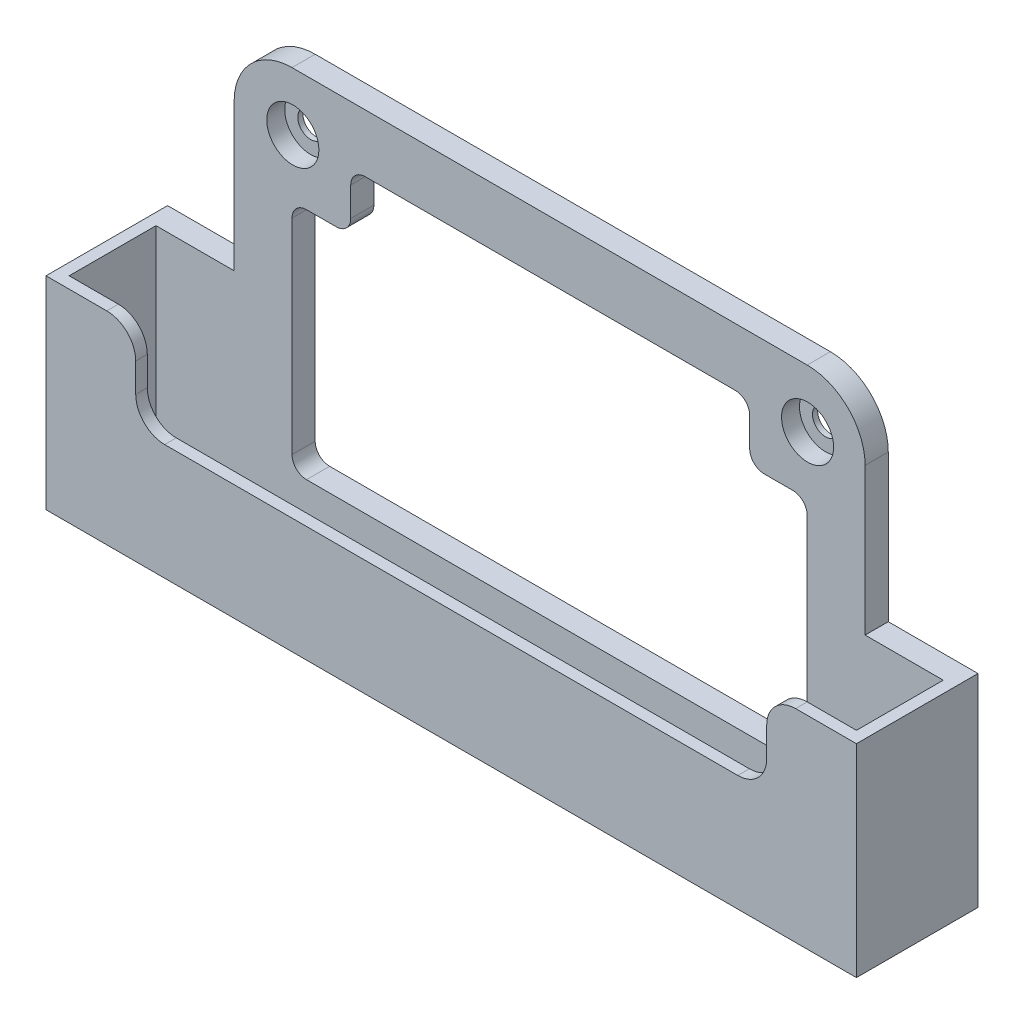
SolidWorks part; units mm, degrees
ref_plane "Front Plane" through (0, 0, 0) normal (0, 0, 1) x (1, 0, 0)
ref_plane "Top Plane" through (0, 0, 0) normal (0, 1, 0) x (1, 0, 0)
ref_plane "Right Plane" through (0, 0, 0) normal (1, 0, 0) x (0, 0, -1)
sketch "Sketch1" plane through (0, 0, 0) normal (0, 0, 1) x (1, 0, 0)
  line L1 (54.5, -70) -> (-54.5, -70)
  line L2 (54.5, -70) -> (54.5, 70)
  line L3 (54.5, 70) -> (-54.5, 70)
  line L4 (-54.5, -70) -> (-54.5, 70)
  line L5 (54.5, -70) -> (-54.5, 70) construction
  line L6 (54.5, 70) -> (-54.5, -70) construction
  point P0 (0, 0)
  point P6 (-44.5, -9.7579)
  point P7 (44.5, -9.7579)
  point P8 (19.5, 58.6849)
  point P9 (-19.5, 58.6849)
  dimension "D1" = 140
  dimension "D2" = 109
  dimension "D3" = 10
  dimension "D4" = 10
  dimension "D5" = 89
  dimension "D6" = 25
  dimension "D7" = 25
extrude "Boss-Extrude1" add sketch "Sketch1" along normal blind 4
hole_wizard "CBORE for M4 Pan Head Machine Screw1" positions "Sketch4" profile "Sketch2" counterbore size "M4" standard "ANSI Metric" end condition through all
sketch "Sketch4" plane through (0, 0, 4) normal (0, 0, 1) x (1, 0, 0)
  point P0 (-19.4083, 58.522)
  point P2 (19.4083, 58.522)
  point P4 (-44.3618, -9.6051)
  point P6 (44.5599, -9.6051)
sketch "Sketch2" plane through (-19.4083, 58.522, 4) normal (1, 0, 0) x (0, -1, 0)
  line L0 (0, 0) -> (0, 4)
  line L1 (0, 4) -> (2.25, 4)
  line L3 (2.25, 4) -> (2.25, 3.1)
  line L4 (2.25, 3.1) -> (4.5, 3.1)
  line L5 (4.5, 3.1) -> (4.5, 0)
  line L7 (4.5, 0) -> (0, 0)
  line L11 (0, -6.35) -> (0, 107.95) construction
  dimension "Thru Hole Dia." = 4.5
  dimension "Thru Hole Depth" = 4
  dimension "C'Bore Dia." = 9
  dimension "C'Bore Depth" = 3.1
sketch "Sketch6" plane through (0, 0, 4) normal (0, 0, 1) x (1, 0, 0)
  line L0 (-29.4083, 70) -> (-29.4083, 0.3949)
  line L1 (54.5, 70) -> (-54.5, 70) construction
  line L2 (-29.4083, 0.3949) -> (-54.5, 0.3949)
  line L3 (-54.5, 70) -> (-54.5, -70) construction
  line L4 (-54.5, 0.3949) -> (-54.5, 70)
  line L5 (-54.5, 70) -> (-29.4083, 70)
  line L6 (29.4083, 70) -> (29.4083, 0.3949)
  line L7 (29.4083, 0.3949) -> (54.5, 0.3949)
  line L8 (54.5, -70) -> (54.5, 70) construction
  line L9 (54.5, 0.3949) -> (54.5, 70)
  line L10 (54.5, 70) -> (29.4083, 70)
  circle A0 centre (-19.4083, 58.522) radius 2.25 construction
  circle A1 centre (19.4083, 58.522) radius 2.25 construction
  circle A2 centre (-44.3618, -9.6051) radius 2.25 construction
  circle A3 centre (44.5599, -9.6051) radius 2.25 construction
  dimension "D1" = 10
  dimension "D2" = 10
  dimension "D3" = 10
  dimension "D4" = 10
extrude "Cut-Extrude1" cut sketch "Sketch6" against normal through all
sketch "Sketch7" plane through (0, 0, 4) normal (0, 0, 1) x (1, 0, 0)
  line L0 (-70, -70) -> (70, -70)
  line L1 (70, -70) -> (70, -35)
  line L2 (70, -35) -> (-70, -35)
  line L3 (-70, -35) -> (-70, -70)
  point P3 (0, -70)
  dimension "D1" = 140
  dimension "D2" = 35
extrude "Boss-Extrude2" add sketch "Sketch7" against normal through all
fillet "Fillet1" radius 10 4 edges at (-54.5, 0.3949, 2) (54.5, 0.3949, 2) (29.4083, 70, 2) (-29.4083, 70, 2)
sketch "Sketch8" plane through (0, 0, 4) normal (0, 0, 1) x (1, 0, 0)
  line L0 (-70, -35) -> (-70, -70)
  line L1 (-70, -70) -> (70, -70)
  line L2 (70, -70) -> (70, -35)
  line L3 (70, -35) -> (68, -35)
  line L4 (70, -35) -> (54.5, -35) construction
  line L5 (68, -35) -> (68, -68)
  line L6 (68, -68) -> (-68, -68)
  line L7 (-68, -68) -> (-68, -35)
  line L8 (-54.5, -35) -> (-70, -35) construction
  line L9 (-68, -35) -> (-70, -35)
  dimension "D1" = 2
  dimension "D2" = 2
  dimension "D3" = 2
extrude "Boss-Extrude3" add sketch "Sketch8" along normal blind 15
sketch "Sketch9" plane through (-70, 0, 0) normal (-1, 0, 0) x (0, 0, 1)
  line L0 (19, -35) -> (19, -70)
  line L1 (19, -70) -> (21, -70)
  line L2 (21, -70) -> (21, -35)
  line L3 (21, -35) -> (19, -35)
  dimension "D1" = 2
extrude "Boss-Extrude4" add sketch "Sketch9" against normal through all
sketch "Sketch10" plane through (0, 0, 4) normal (0, 0, 1) x (1, 0, 0)
  line L0 (-19.4083, 48.522) -> (-9.4083, 48.522)
  line L1 (19.4083, 48.522) -> (19.4083, -9.6051)
  line L2 (19.4083, -9.6051) -> (34.5599, -9.6051)
  line L3 (34.5599, -9.6051) -> (34.5599, -19.6051)
  line L4 (34.5599, -19.6051) -> (44.5, -19.6051)
  line L5 (44.5, -19.6051) -> (44.5, -60)
  line L6 (44.5, -60) -> (-44.5, -60)
  line L7 (-44.5, -60) -> (-44.5, -19.6051)
  line L8 (-44.5, -19.6051) -> (-34.3618, -19.6051)
  line L9 (-34.3618, -19.6051) -> (-34.3618, -9.6051)
  line L10 (-34.3618, -9.6051) -> (-19.4083, -9.6051)
  line L11 (-19.4083, -9.6051) -> (-19.4083, 48.522)
  line L12 (-29.4083, 0.3949) -> (-29.4083, 60) construction
  line L13 (29.4083, 60) -> (29.4083, 0.3949) construction
  line L14 (29.4083, 0.3949) -> (44.5, 0.3949) construction
  line L15 (-44.5, 0.3949) -> (-29.4083, 0.3949) construction
  line L16 (54.5, -35) -> (54.5, -9.6051) construction
  line L17 (-54.5, -9.6051) -> (-54.5, -35) construction
  line L18 (-54.5, -9.6051) -> (-54.5, -35) construction
  line L19 (70, -70) -> (-70, -70) construction
  line L20 (-9.4083, 48.522) -> (-9.4083, 60)
  line L21 (-9.4083, 60) -> (9.4083, 60)
  line L22 (9.4083, 60) -> (9.4083, 48.522)
  line L23 (9.4083, 48.522) -> (19.4083, 48.522)
  line L24 (19.4083, 70) -> (-19.4083, 70) construction
  circle A0 centre (-19.4083, 58.522) radius 4.5 construction
  circle A1 centre (44.5599, -9.6051) radius 2.25 construction
  circle A2 centre (-44.3618, -9.6051) radius 2.25 construction
  circle A3 centre (-19.4083, 58.522) radius 2.25 construction
  circle A4 centre (19.4083, 58.522) radius 2.25 construction
  dimension "D1" = 10
  dimension "D2" = 10
  dimension "D3" = 10
  dimension "D4" = 10
  dimension "D5" = 10
  dimension "D6" = 10
  dimension "D7" = 10
  dimension "D8" = 10
  dimension "D9" = 10
  dimension "D10" = 10
  dimension "D11" = 10
  dimension "D12" = 10
  dimension "D13" = 10
  dimension "D14" = 10
  dimension "D15" = 10
extrude "Cut-Extrude3" cut sketch "Sketch10" against normal through all
sketch "Sketch11" plane through (0, 0, 21) normal (0, 0, 1) x (1, 0, 0)
  line L0 (-54.5, -35) -> (-54.5, -50)
  line L1 (70, -35) -> (-70, -35) construction
  line L2 (-54.5, -50) -> (54.5, -50)
  line L3 (54.5, -50) -> (54.5, -35)
  line L4 (54.5, -35) -> (-54.5, -35)
  line L7 (-54.5, -9.6051) -> (-54.5, -35) construction
  line L8 (54.5, -35) -> (54.5, -9.6051) construction
  line L9 (70, -70) -> (-70, -70) construction
  dimension "D1" = 0
  dimension "D2" = 0
  dimension "D3" = 20
extrude "Cut-Extrude4" cut sketch "Sketch11" against normal up to surface (2 mm away) up to face at (17, -51.5, 19)
fillet "Fillet6" radius 5 5 edges at (-54.5, -50, 20) (54.5, -50, 20) (54.5, -35, 20) (-54.5, -35, 20)
sketch "Sketch13" plane through (0, 0, 0) normal (1, 0, 0) x (0, 0, -1)
  line L0 (0, 0.3949) -> (-4, 0.3949)
  line L1 (-4, 0.3949) -> (-4, 73.9644)
  line L2 (-4, 73.9644) -> (0, 73.9644)
  line L3 (0, 73.9644) -> (0, 0.3949)
extrude "Cut-Extrude5" cut sketch "Sketch13" against normal up to surface and the other way up to surface up to face at (-29.4083, 30.1974, 2) other way up to face at (29.4083, 30.1974, 2)
sketch "Sketch14" plane through (19.4083, 0, 0) normal (-1, 0, 0) x (0, 0, 1)
  line L0 (0, 0.3949) -> (4, 0.3949)
  line L1 (4, 0.3949) -> (4, -9.6051)
  line L2 (4, -9.6051) -> (0, -9.6051)
  line L3 (0, -9.6051) -> (0, 0.3949)
extrude "Boss-Extrude5" add sketch "Sketch14" along normal up to surface (38.8166 mm away) up to face at (-19.4083, -4.6051, 2)
fillet "Fillet9" radius 2.5 8 edges at (-44.5, -60, 2) (44.5, -60, 2) (44.5, -19.6051, 2) (34.5599, -19.6051, 2) (34.5599, -9.6051, 2) (-44.5, -19.6051, 2) (-34.3618, -19.6051, 2) (-34.3618, -9.6051, 2)
